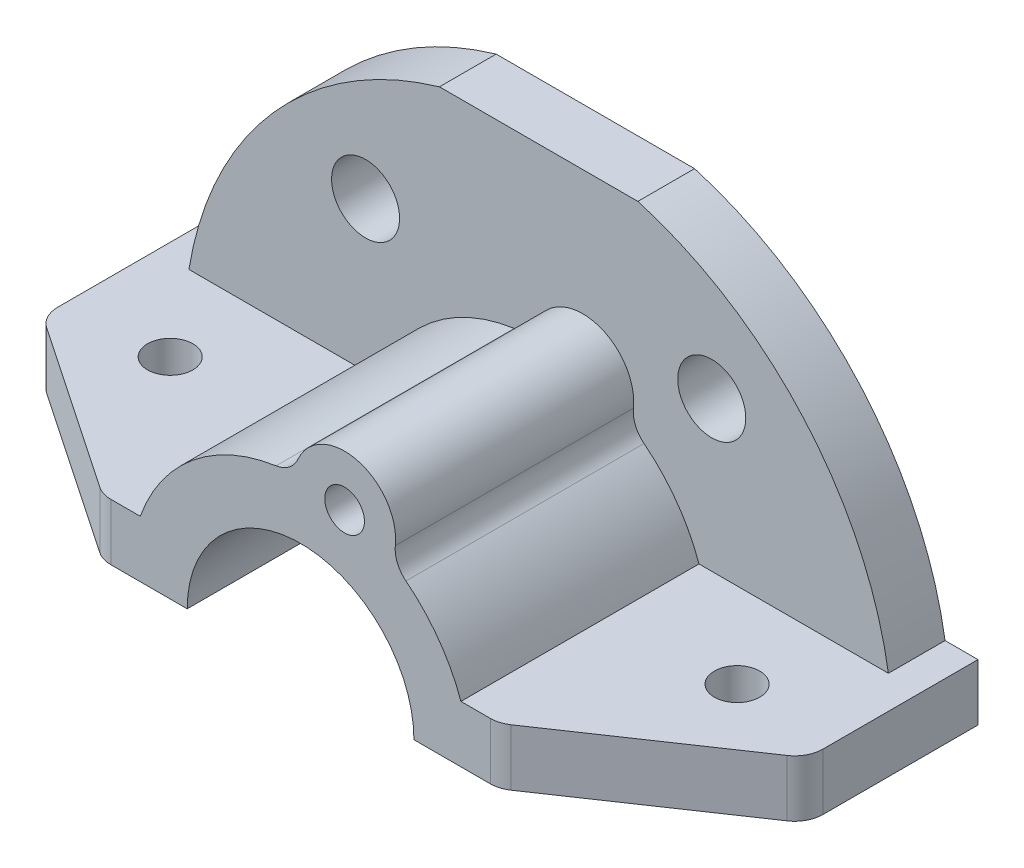
SolidWorks part; units mm, degrees
ref_plane "Front Plane" through (0, 0, 0) normal (0, 0, 1) x (1, 0, 0)
ref_plane "Top Plane" through (0, 0, 0) normal (0, 1, 0) x (1, 0, 0)
ref_plane "Right Plane" through (0, 0, 0) normal (1, 0, 0) x (0, 0, -1)
sketch "Sketch1" plane through (0, 0, 0) normal (0, 0, 1) x (1, 0, 0)
  line L0 (0, 0) -> (0, 36.1793) construction
  line L1 (-51.3204, 0) -> (51.3204, 0) construction
  line L2 (-28.2843, 10) -> (-67.5, 10)
  line L3 (-67.5, 10) -> (-67.5, 0)
  line L4 (-67.5, 0) -> (-20, 0)
  line L5 (28.2843, 10) -> (67.5, 10)
  line L6 (67.5, 10) -> (67.5, 0)
  line L7 (67.5, 0) -> (20, 0)
  line L8 (0, 0) -> (7.7646, 28.9778) construction
  arc A0 (20, 0) -> (-20, 0) centre (0, 0) ccw
  arc A1 (28.2843, 10) -> (16.0101, 25.3708) centre (0, 0) ccw
  arc A3 (16.0101, 25.3708) -> (-1.1798, 29.9768) centre (7.7646, 28.9778) ccw
  arc A4 (-1.1798, 29.9768) -> (-28.2843, 10) centre (0, 0) ccw
  circle A5 centre (7.7646, 28.9778) radius 3.5
  point P8 (0, 0)
  dimension "D1" = 7
  dimension "D2" = 9
  dimension "D4" = 30
  dimension "D9" = 20
  dimension "D3" = 30
  dimension "D5" = 10
  dimension "D6" = 10
  dimension "D7" = 135
  dimension "D8" = 67.5
  dimension "D10" = 75
extrude "Boss-Extrude1" add sketch "Sketch1" against normal blind 52
ref_plane "Plane1" through (0, 0, -42) normal (0, 0, 1) x (1, 0, 0)
sketch "Sketch2" plane through (0, 0, -42) normal (0, 0, 1) x (1, 0, 0)
  line L0 (-122.1494, 0) -> (122.1494, 0) construction
  line L1 (0, 0) -> (0, 92.9099) construction
  line L3 (0, 0) -> (30.5324, 36.3871) construction
  line L4 (17.5, 60) -> (-17.5, 60)
  line L5 (67.5, 10) -> (28.2843, 10) construction
  line L6 (-28.2843, 10) -> (-67.5, 10) construction
  line L7 (61.6948, 10) -> (28.2843, 10)
  line L8 (-28.2843, 10) -> (-61.6948, 10)
  arc A0 (61.6948, 10) -> (17.5, 60) centre (0, 0) ccw
  circle A1 centre (0, 0) radius 47.5 construction
  circle A3 centre (30.5324, 36.3871) radius 6
  circle A4 centre (-30.5324, 36.3871) radius 6
  arc A5 (-17.5, 60) -> (-61.6948, 10) centre (0, 0) ccw
  arc A6 (28.2843, 10) -> (16.0101, 25.3708) centre (0, 0) ccw construction
  arc A7 (16.0101, 25.3708) -> (-1.1798, 29.9768) centre (7.7646, 28.9778) ccw construction
  arc A8 (-1.1798, 29.9768) -> (-28.2843, 10) centre (0, 0) ccw construction
  arc A9 (28.2843, 10) -> (16.0101, 25.3708) centre (0, 0) ccw
  arc A10 (16.0101, 25.3708) -> (-1.1798, 29.9768) centre (7.7646, 28.9778) ccw
  arc A11 (-1.1798, 29.9768) -> (-28.2843, 10) centre (0, 0) ccw
  point P6 (0, 0)
  point P16 (0, 58.0108)
  dimension "D1" = 125
  dimension "D3" = 12
  dimension "D4" = 95
extrude "Boss-Extrude2" add sketch "Sketch2" against normal blind 10
sketch "Sketch3" plane through (0, 0, 0) normal (0, 1, 0) x (1, 0, 0)
  line L0 (0, 0) -> (0, 63.4148) construction
  line L1 (0, 0) -> (102.0602, 0) construction
  line L2 (67.5, 52) -> (61.6948, 52) construction
  line L3 (67.5, 22) -> (35, 0)
  line L4 (67.5, 52) -> (67.5, 0) construction
  line L5 (35, 0) -> (67.5, 0)
  line L6 (67.5, 0) -> (67.5, 22)
  line L7 (-67.5, 0) -> (-67.5, 22)
  line L8 (-35, 0) -> (-67.5, 0)
  line L9 (-67.5, 22) -> (-35, 0)
  circle A0 centre (50, 27) radius 4
  circle A1 centre (-50, 27) radius 4
  dimension "D1" = 8
  dimension "D2" = 25
  dimension "D3" = 30
  dimension "D4" = 70
  dimension "D5" = 100
extrude "Cut-Extrude1" cut sketch "Sketch3" along normal blind 10
fillet "Fillet1" radius 5 6 edges at (-1.1798, 29.9768, -21) (16.0101, 25.3708, -21) (67.5, 5, -22) (35, 5, 0) (-35, 5, 0) (-67.5, 5, -22)
